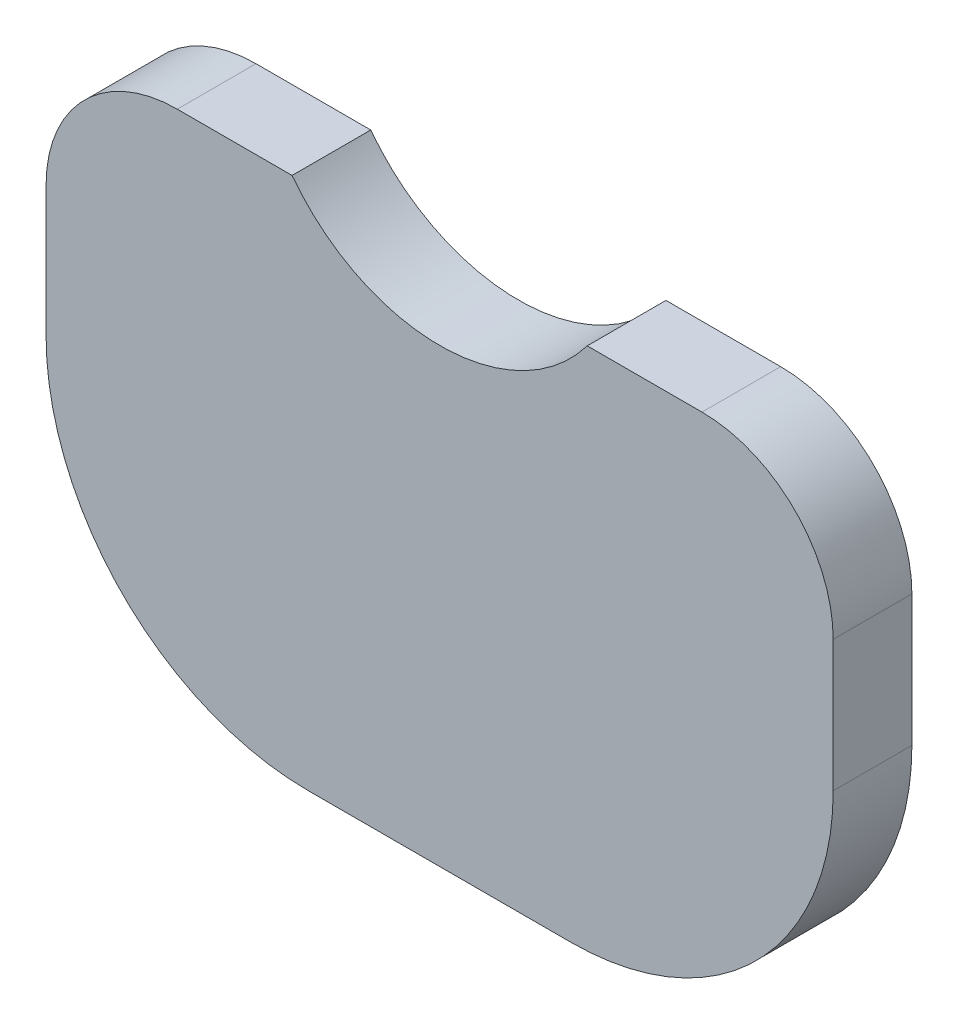
SolidWorks part; units mm, degrees
ref_plane "前视基准面" through (0, 0, 0) normal (0, 0, 1) x (1, 0, 0)
ref_plane "上视基准面" through (0, 0, 0) normal (0, 1, 0) x (1, 0, 0)
ref_plane "右视基准面" through (0, 0, 0) normal (1, 0, 0) x (0, 0, -1)
other "Configuration Table"
sketch "草图1" plane through (0, 0, 0) normal (0, 0, 1) x (1, 0, 0)
  line L1 (10, -20) -> (-10, -20)
  line L2 (30, 0) -> (30, 10)
  line L3 (20, 20) -> (-20, 20)
  line L4 (-30, 0) -> (-30, 10)
  line L5 (30, -20) -> (-30, 20) construction
  line L6 (30, 20) -> (-30, -20) construction
  arc A0 (-30, 10) -> (-20, 20) centre (-20, 10) cw
  arc A1 (30, 10) -> (20, 20) centre (20, 10) ccw
  circle A4 centre (0, 28.5) radius 14.1
  arc A5 (30, 0) -> (10, -20) centre (10, 0) cw
  arc A6 (-10, -20) -> (-30, 0) centre (-10, 0) cw
  point P0 (0, 0)
  dimension "D3" = 10
  dimension "D4" = 28.2
  dimension "D6" = 20
  dimension "D1" = 60
  dimension "D2" = 40
  dimension "D5" = 8.5
extrude "凸台-拉伸1" add sketch "草图1" along normal blind 6 contours A6 L1 A5 L2 A1 L3 A4 A0 L4
sketch "草图3" plane through (0, 0, 0) normal (0, 0, 1) x (1, 0, 0)
  line L0 (20, 20) -> (11.2499, 20) construction
  line L1 (0, 14.4) -> (0, -20) construction
  line L2 (10, -20) -> (-10, -20) construction
  circle A0 centre (-12.5, 0) radius 7.5
  circle A1 centre (12.5, 0) radius 7.5
  arc A2 (-11.2499, 20) -> (11.2499, 20) centre (0, 28.5) ccw construction
  dimension "D1" = 15
  dimension "D2" = 15
  dimension "D3" = 20
  dimension "D4" = 12.5
  dimension "D5" = 12.5
extrude "凸台-拉伸2" add sketch "草图3" against normal blind 6.5
